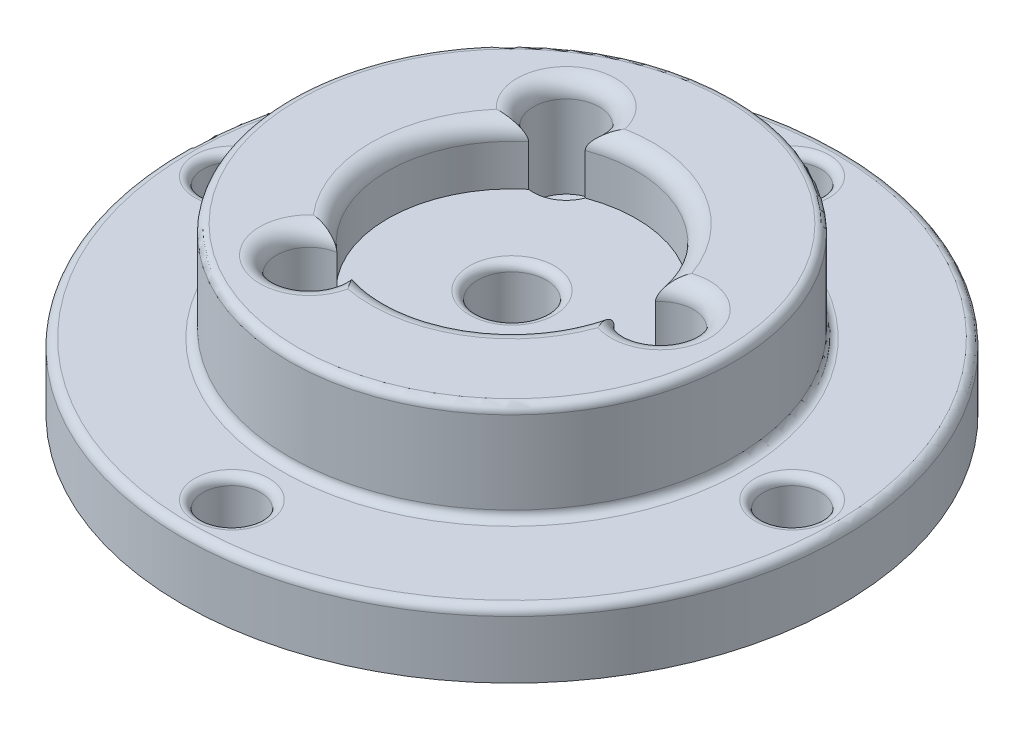
SolidWorks part; units mm, degrees
ref_plane "Front Plane" through (0, 0, 0) normal (0, 0, 1) x (1, 0, 0)
ref_plane "Top Plane" through (0, 0, 0) normal (0, 1, 0) x (1, 0, 0)
ref_plane "Right Plane" through (0, 0, 0) normal (1, 0, 0) x (0, 0, -1)
sketch "Sketch2" plane through (0, 0, 0) normal (0, 1, 0) x (1, 0, 0)
  circle A0 centre (0, 0) radius 13.5
  dimension "D1" = 27
extrude "Boss-Extrude1" add sketch "Sketch2" along normal blind 6
sketch "Sketch3" plane through (0, 6, 0) normal (0, 1, 0) x (1, 0, 0)
  circle A0 centre (0, 0) radius 7.55
  dimension "D1" = 15.1
extrude "Cut-Extrude1" cut sketch "Sketch3" against normal blind 3.5
sketch "Sketch5" plane through (0, 6, 0) normal (0, 1, 0) x (1, 0, 0)
  circle A0 centre (0, 0) radius 9 construction
  circle A1 centre (9, 0) radius 2
  circle A2 centre (-4.5, -7.7942) radius 2
  circle A3 centre (-4.5, 7.7942) radius 2
  dimension "D1" = 3
extrude "Cut-Extrude3" cut sketch "Sketch5" against normal up to surface (6 mm away) up to face at (0, 0, 13.5)
fillet "Fillet1" radius 1 6 edges at (-5.5, 6, 9.5263) (3.775, 6, 6.5385) (11, 6, 0) (3.775, 6, -6.5385) (-5.5, 6, -9.5263) (-7.55, 6, 0)
sketch "Sketch6" plane through (0, 0, 0) normal (0, -1, 0) x (1, 0, 0)
  circle A0 centre (0, 0) radius 20
  dimension "D1" = 40
extrude "Boss-Extrude2" add sketch "Sketch6" along normal blind 4
sketch "Sketch9" plane through (0, 2.5, 0) normal (0, 1, 0) x (1, 0, 0)
  circle A0 centre (0, 0) radius 2.0828
extrude "Cut-Extrude6" cut sketch "Sketch9" against normal up to surface (6.5 mm away) up to face at (0, -4, -20)
fillet "Fillet5" radius 0.5 4 edges at (0, 6, 13.5) (0, 0, 13.5) (0, 0, -20) (0, 2.5, 2.0828)
sketch "Sketch10" plane through (0, 0, 0) normal (0, 1, 0) x (1, 0, 0)
  circle A0 centre (0, 0) radius 17 construction
  circle A1 centre (0, -17) radius 1.75
  circle A2 centre (-17, 0) radius 1.75
  circle A3 centre (0, 17) radius 1.75
  circle A4 centre (17, 0) radius 1.75
  dimension "D1" = 4
  dimension "D2" = 34
  dimension "D3" = 3.5
extrude "Cut-Extrude7" cut sketch "Sketch10" against normal blind 4
fillet "Fillet6" radius 0.5 4 edges at (17, 0, 1.75) (0, 0, -15.25) (-17, 0, 1.75) (0, 0, 18.75)
